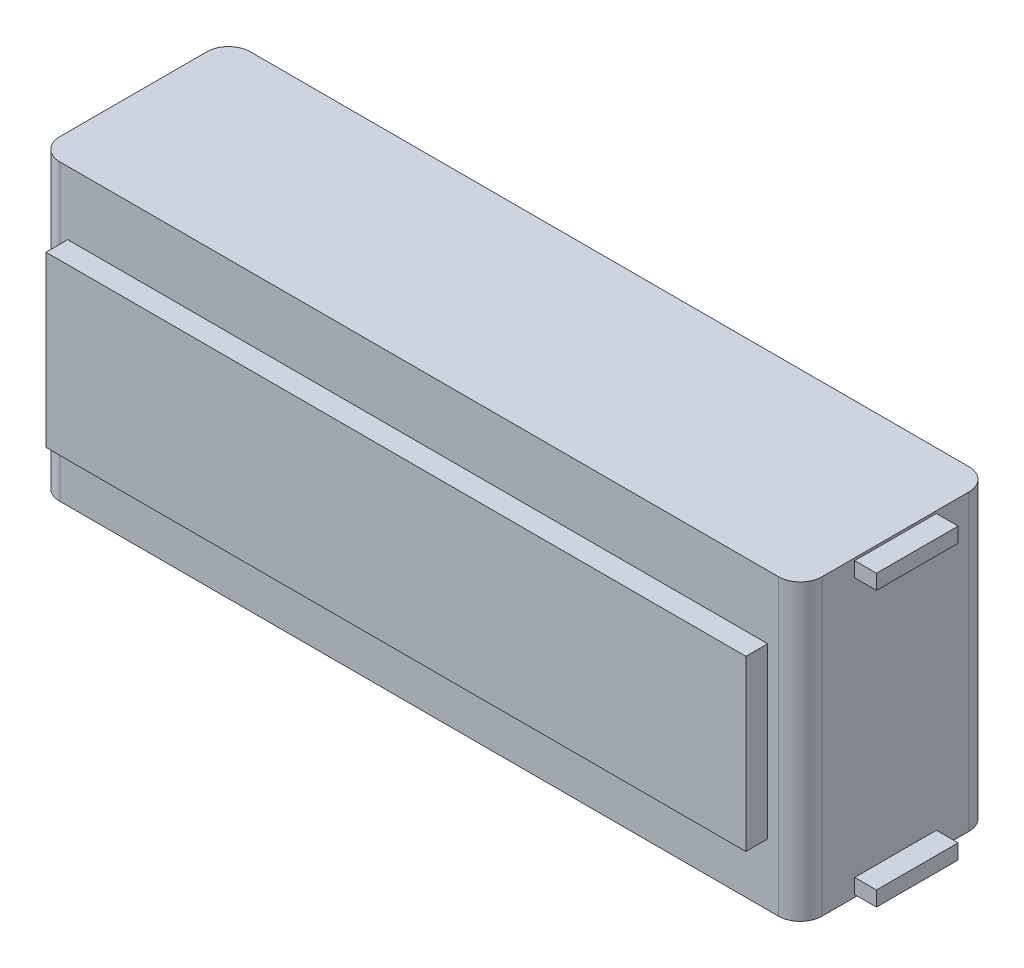
SolidWorks part; units mm, degrees
ref_plane "Front Plane" through (0, 0, 0) normal (0, 0, 1) x (1, 0, 0)
ref_plane "Top Plane" through (0, 0, 0) normal (0, 1, 0) x (1, 0, 0)
ref_plane "Right Plane" through (0, 0, 0) normal (1, 0, 0) x (0, 0, -1)
sketch "Sketch1" plane through (0, 0, 0) normal (0, 0, 1) x (1, 0, 0)
  line L1 (-44.45, -17.145) -> (44.45, -17.145)
  line L2 (-44.45, -17.145) -> (-44.45, 17.145)
  line L3 (-44.45, 17.145) -> (44.45, 17.145)
  line L4 (44.45, -17.145) -> (44.45, 17.145)
  line L5 (-44.45, -17.145) -> (44.45, 17.145) construction
  line L6 (-44.45, 17.145) -> (44.45, -17.145) construction
  point P0 (0, 0)
  dimension "D1" = 88.9
  dimension "D2" = 34.29
extrude "Boss-Extrude1" add sketch "Sketch1" along normal blind 22.225
fillet "Fillet1" radius 2.54 4 edges at (44.45, 0, 0) (44.45, 0, 22.225) (-44.45, 0, 0) (-44.45, 0, 22.225)
sketch "Sketch2" plane through (44.45, 0, 0) normal (1, 0, 0) x (0, 0, -1)
  line L0 (-19.685, 0) -> (-2.54, 0) construction
  line L1 (-19.685, 17.145) -> (-19.685, -17.145) construction
  line L2 (-2.54, -17.145) -> (-2.54, 17.145) construction
  line L3 (-11.1125, 0) -> (-11.1125, 15.9968) construction
  line L5 (-15.8754, 15.1301) -> (-6.3496, 15.1301)
  line L6 (-15.8754, 15.1301) -> (-15.8754, 16.8636)
  line L7 (-15.8754, 16.8636) -> (-6.3496, 16.8636)
  line L8 (-6.3496, 15.1301) -> (-6.3496, 16.8636)
  line L9 (-15.8754, 15.1301) -> (-6.3496, 16.8636) construction
  line L10 (-15.8754, 16.8636) -> (-6.3496, 15.1301) construction
extrude "Boss-Extrude2" add sketch "Sketch2" along normal blind 2.54
mirror "Mirror1" about plane through (0, 0, 0) normal (0, 1, 0) of "Boss-Extrude2"
sketch "Sketch3" plane through (0, 0, 22.225) normal (0, 0, 1) x (1, 0, 0)
  line L1 (40.6525, -9.9631) -> (-40.9796, -9.9631)
  line L2 (40.6525, -9.9631) -> (40.6525, 9.7468)
  line L3 (40.6525, 9.7468) -> (-40.9796, 9.7468)
  line L4 (-40.9796, -9.9631) -> (-40.9796, 9.7468)
extrude "Boss-Extrude3" add sketch "Sketch3" along normal blind 2.54
